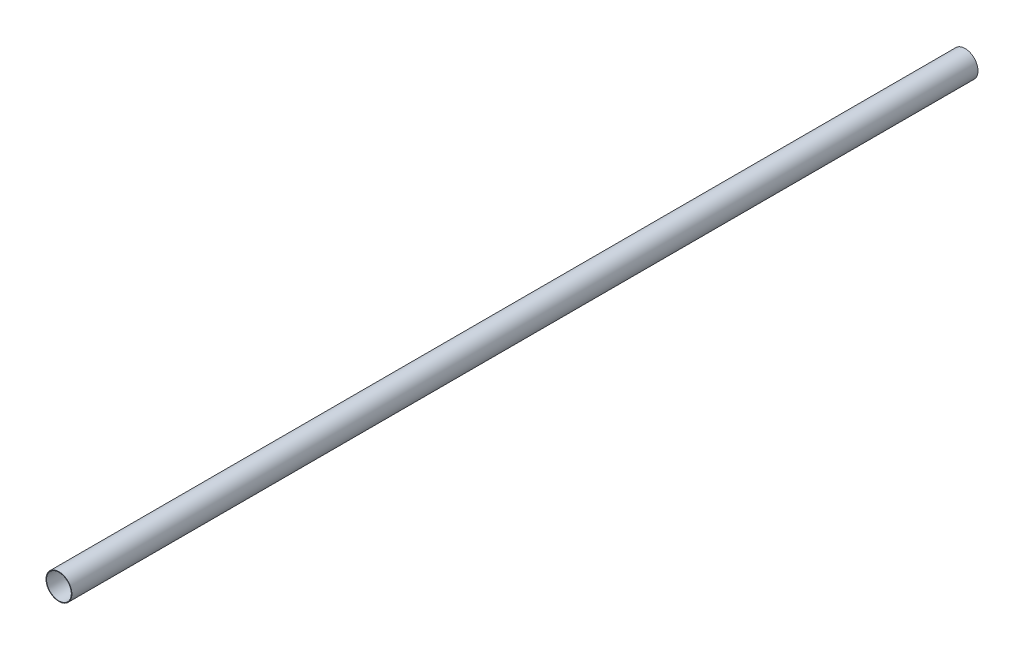
SolidWorks part; units mm, degrees
ref_plane "Front Plane" through (0, 0, 0) normal (0, 0, 1) x (1, 0, 0)
ref_plane "Top Plane" through (0, 0, 0) normal (0, 1, 0) x (1, 0, 0)
ref_plane "Right Plane" through (0, 0, 0) normal (1, 0, 0) x (0, 0, -1)
sketch "Sketch1" plane through (0, 0, 0) normal (0, 0, 1) x (1, 0, 0)
  circle A0 centre (0, 0) radius 15
  circle A1 centre (0, 0) radius 14.35
  dimension "D1" = 30
  dimension "D2" = 28.7
extrude "Boss-Extrude1" add sketch "Sketch1" along normal blind 1050
